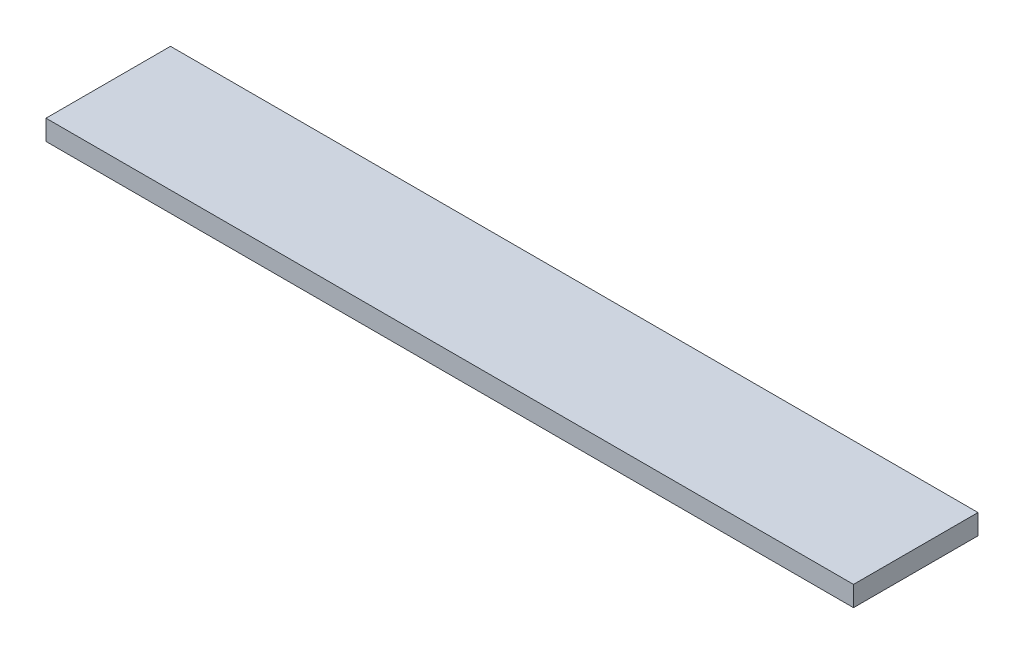
SolidWorks part; units mm, degrees
material "Pine"
ref_plane "Front Plane" through (0, 0, 0) normal (0, 0, 1) x (1, 0, 0)
ref_plane "Top Plane" through (0, 0, 0) normal (0, 1, 0) x (1, 0, 0)
ref_plane "Right Plane" through (0, 0, 0) normal (1, 0, 0) x (0, 0, -1)
sketch "Sketch1" plane through (0, 0, 0) normal (0, 1, 0) x (1, 0, 0)
  line L1 (-6705.6, 7711.44) -> (-5181.6, 7711.44)
  line L2 (-6705.6, 7711.44) -> (-6705.6, 7476.49)
  line L3 (-6705.6, 7476.49) -> (-5181.6, 7476.49)
  line L4 (-5181.6, 7711.44) -> (-5181.6, 7476.49)
  dimension "D1" = 1524
  dimension "D2" = 234.95
extrude "Boss-Extrude1" add sketch "Sketch1" along normal blind 38.1 contours L1 L4 L3 L2
